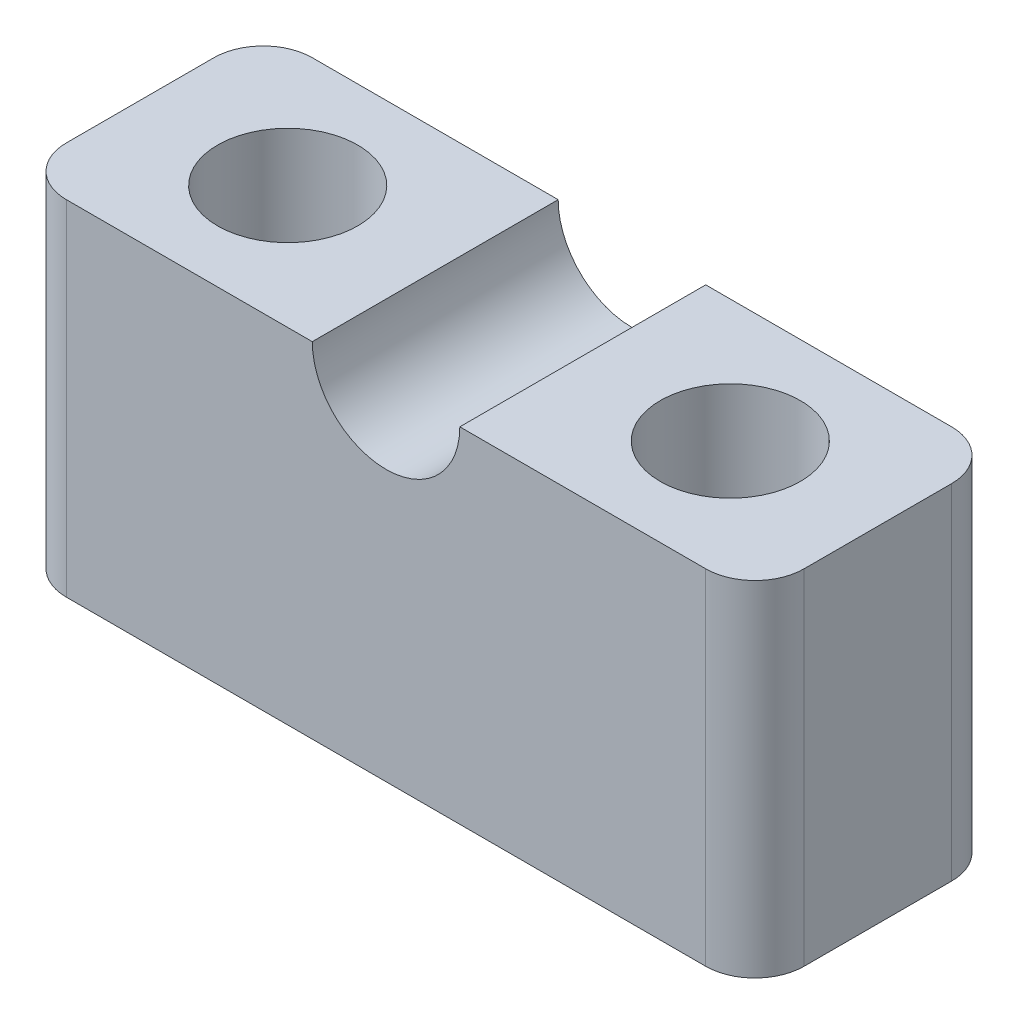
SolidWorks part; units mm, degrees
ref_plane "Front Plane" through (0, 0, 0) normal (0, 0, 1) x (1, 0, 0)
ref_plane "Top Plane" through (0, 0, 0) normal (0, 1, 0) x (1, 0, 0)
ref_plane "Right Plane" through (0, 0, 0) normal (1, 0, 0) x (0, 0, -1)
sketch "Sketch1" plane through (0, 0, 0) normal (0, 1, 0) x (1, 0, 0)
  line L1 (-4.0594, -2.1535) -> (10.9406, -2.1535)
  line L2 (-4.0594, -2.1535) -> (-4.0594, 2.8465)
  line L3 (-4.0594, 2.8465) -> (10.9406, 2.8465)
  line L4 (10.9406, -2.1535) -> (10.9406, 2.8465)
  dimension "D1" = 5
  dimension "D2" = 15
extrude "Boss-Extrude1" add sketch "Sketch1" along normal blind 7
sketch "Sketch2" plane through (0, 0, -2.8465) normal (0, 0, -1) x (-1, 0, 0)
  line L0 (-10.9406, 7) -> (4.0594, 7) construction
  circle A0 centre (-3.4406, 7) radius 1.5
  dimension "D1" = 3
extrude "Cut-Extrude1" cut sketch "Sketch2" against normal through all
sketch "Sketch3" plane through (0, 7, 0) normal (0, 1, 0) x (1, 0, 0)
  line L0 (-4.0594, 2.8465) -> (-4.0594, -2.1535) construction
  line L1 (1.9406, 2.8465) -> (-4.0594, 2.8465) construction
  line L2 (10.9406, 2.8465) -> (4.9406, 2.8465) construction
  circle A0 centre (7.9406, 0.3465) radius 1.425
  circle A1 centre (-1.0594, 0.3465) radius 1.425
  point P4 (0, 0)
  point P5 (0, 0)
  point P6 (0, 0)
  point P9 (-4.0594, 0.3465)
  point P12 (-1.0594, 2.8465)
  point P13 (0, 0)
  point P14 (0, 0)
  point P17 (7.9406, 2.8465)
  dimension "D1" = 2.85
  dimension "D2" = 2.85
extrude "Cut-Extrude2" cut sketch "Sketch3" against normal through all
fillet "Fillet1" radius 1 4 edges at (-4.0594, 3.5, 2.1535) (10.9406, 3.5, 2.1535) (10.9406, 3.5, -2.8465) (-4.0594, 3.5, -2.8465)
